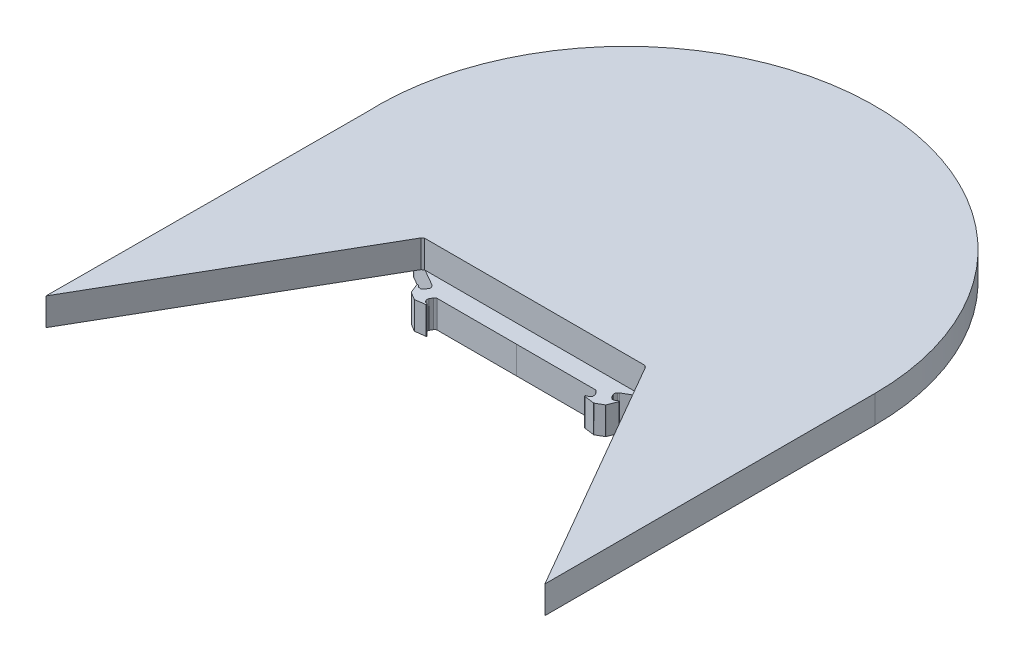
SolidWorks part; units mm, degrees
ref_plane "Plan de face" through (0, 0, 0) normal (0, 0, 1) x (1, 0, 0)
ref_plane "Plan de dessus" through (0, 0, 0) normal (0, 1, 0) x (1, 0, 0)
ref_plane "Plan de droite" through (0, 0, 0) normal (1, 0, 0) x (0, 0, -1)
sketch "Esquisse1" plane through (0, 0, 0) normal (0, 1, 0) x (1, 0, 0)
  line L0 (-45.2608, -54.9089) -> (-45.6072, -54.7089) construction
  line L26 (-150.2608, -236.7743) -> (-20.2608, -11.6077) construction
  line L32 (-20.2608, -11.6077) -> (-20.6666, -11.5106) construction
  line L34 (-0.2608, -11.6077) -> (0.0368, 50.714) construction
  line L35 (-0.2608, -11.6077) -> (-0.2608, -11.2077) construction
  line L38 (-20.2608, -11.6077) -> (19.7392, -11.6077) construction
  line L40 (-45.6072, -54.7089) -> (-20.6666, -11.5106)
  line L41 (-20.2608, -11.6077) -> (-20.2608, -11.2077) construction
  line L53 (-45.6072, -54.7089) -> (-45.3945, 3.1355)
  line L54 (-20.6666, -11.5106) -> (-20.2608, -11.2077)
  line L55 (-20.2608, -11.2077) -> (-0.2608, -11.2077)
  line L56 (19.7392, -11.6077) -> (19.7392, -11.2077) construction
  line L57 (19.7392, -11.6077) -> (20.0857, -11.4077) construction
  line L58 (19.7392, -11.6077) -> (24.7392, -20.2679) construction
  line L59 (44.7392, -54.9089) -> (45.0857, -54.7089) construction
  line L60 (19.7392, -11.6077) -> (149.7392, -236.7743) construction
  line L62 (19.7392, -11.2077) -> (-0.2608, -11.2077)
  line L63 (45.0857, -54.7089) -> (45.0857, 5.2911)
  line L64 (19.7392, -11.2077) -> (20.0857, -11.4077)
  line L65 (20.0857, -11.4077) -> (45.0857, -54.7089)
  arc A0 (-45.3945, 3.1355) -> (45.0857, 5.2911) centre (-0.1801, 5.2911) cw
  dimension "D1" = 50
  dimension "D2" = 90
extrude "Boss.-Extru.1" add sketch "Esquisse1" along normal blind 5
sketch "Esquisse3" plane through (0, 0, 0) normal (0, -1, 0) x (1, 0, 0)
  line L12 (-17.9029, 14.1237) -> (-18.1032, 14.4706) construction
  line L30 (-18.7932, 13.9216) -> (-18.7925, 13.9225) construction
  line L31 (-18.7152, 14.9834) -> (-18.3366, 14.8537) construction
  line L32 (-18.3209, 16.1348) -> (-19.1095, 13.832) construction
  line L33 (-18.2862, 16.1971) -> (-17.9773, 15.9429) construction
  line L34 (-16.5624, 17.1923) -> (-16.5624, 16.7923) construction
  line L35 (-13.9437, 16.5594) -> (-14.3345, 16.4943) construction
  line L36 (-14.9584, 15.8237) -> (-15.1584, 16.1701) construction
  line L37 (-17.4797, 13.7907) -> (-17.1333, 13.9907) construction
  line L38 (-17.6297, 14.0505) -> (-17.3297, 13.5309) construction
  line L39 (-14.8816, 15.2907) -> (-15.228, 15.0907) construction
  line L40 (-14.7316, 15.0309) -> (-15.0316, 15.5505) construction
  line L41 (-17.4306, 16.7057) -> (-17.2327, 16.3629) construction
  line L42 (-16.6295, 17.1682) -> (-18.2317, 16.2432) construction
  line L43 (-15.9306, 14.1077) -> (-20.9306, 22.7679) construction
  line L44 (-17.7511, 14.1437) -> (-17.6487, 14.5257) construction
  line L45 (-15.2967, 16.9571) -> (-15.3494, 16.5594) construction
  line L46 (-14.1025, 16.7228) -> (-16.491, 17.1913) construction
  line L47 (-15.0516, 15.7022) -> (-15.4278, 15.8237) construction
  line L48 (-17.6297, 14.0505) -> (-17.2833, 14.2505) construction
  line L49 (-15.0316, 15.5505) -> (-15.378, 15.3505) construction
  line L50 (-17.1333, 13.9907) -> (-17.2731, 14.2328)
  line L51 (-17.2995, 14.2627) -> (-17.6165, 14.5014)
  line L52 (-17.6887, 14.5208) -> (-18.0751, 14.474)
  line L53 (-18.1253, 14.453) -> (-18.4956, 14.1586)
  line L54 (-18.6506, 14.2743) -> (-17.9898, 15.9119)
  line L55 (-17.9486, 15.9602) -> (-16.5924, 16.7743)
  line L56 (-16.5277, 16.7877) -> (-14.7164, 16.5454)
  line L57 (-14.693, 16.3532) -> (-15.1329, 16.1801)
  line L58 (-15.1752, 16.1485) -> (-15.4031, 15.8555)
  line L59 (-15.4236, 15.7836) -> (-15.3802, 15.3716)
  line L60 (-15.3674, 15.3321) -> (-15.228, 15.0907)
  line L61 (-15.228, 15.0907) -> (-15.0498, 14.782)
  line L62 (-20.2608, 11.6077) -> (-11.6005, 16.6077) construction
  line L63 (-17.1333, 13.9907) -> (-16.9608, 13.692)
  line L66 (-24.5749, 6.5161) -> (23.9303, 6.572)
  line L68 (-20.6666, 11.5106) -> (-20.2608, 11.2077) construction
  line L69 (-20.2608, 11.6077) -> (-20.0679, 11.2736) construction
  line L70 (-20.2608, 11.6077) -> (-25.2608, 20.2679) construction
  line L71 (-17.4029, 13.2577) -> (-17.21, 12.9236) construction
  line L73 (-25.076, 8.3821) -> (-17.2804, 12.8829)
  line L74 (-17.3097, 13.3791) -> (-16.9455, 13.2743) construction
  line L75 (-17.161, 12.9885) -> (-16.9981, 13.2046)
  line L76 (-16.9267, 13.3596) -> (-16.9165, 13.4062)
  line L77 (-14.8435, 14.6074) -> (-14.7364, 14.5673)
  line L79 (-14.5066, 15.324) -> (-14.6686, 14.542) construction
  line L80 (-14.5963, 14.542) -> (-0.2608, 14.542)
  line L81 (-0.2608, 11.6077) -> (-0.2608, 28.9666) construction
  line L82 (-0.2608, 14.542) -> (-0.3638, 6.544) construction
  line L84 (19.566, 11.7077) -> (19.366, 11.3612) construction
  line L85 (16.8814, 13.2577) -> (16.6814, 12.9112) construction
  line L86 (16.7882, 13.3791) -> (16.4018, 13.2756) construction
  line L87 (16.8082, 13.5309) -> (16.4618, 13.7309) construction
  line L88 (16.8082, 13.5309) -> (17.1082, 14.0505) construction
  line L89 (17.1082, 14.0505) -> (16.7618, 14.2505) construction
  line L90 (17.2296, 14.1437) -> (17.1261, 14.53) construction
  line L91 (17.3814, 14.1237) -> (17.5814, 14.4701) construction
  line L92 (18.2717, 13.9216) -> (18.271, 13.9225) construction
  line L93 (17.7994, 16.1348) -> (17.421, 16.0052) construction
  line L94 (18.588, 13.832) -> (17.7994, 16.1348) construction
  line L95 (15.9695, 17.1913) -> (16.0465, 16.7988) construction
  line L96 (13.4222, 16.5594) -> (13.8167, 16.4937) construction
  line L97 (14.4369, 15.8237) -> (14.6369, 16.1701) construction
  line L98 (14.5301, 15.7022) -> (14.9164, 15.8058) construction
  line L99 (14.5101, 15.5505) -> (14.8565, 15.3505) construction
  line L100 (14.2101, 15.0309) -> (14.5565, 14.8309) construction
  line L101 (13.9851, 15.324) -> (14.1922, 14.5513) construction
  line L102 (14.2191, 14.5719) -> (14.5407, 14.8188)
  line L103 (14.5664, 14.8481) -> (14.8465, 15.3332)
  line L104 (14.8591, 15.3702) -> (14.911, 15.7647)
  line L105 (14.8912, 15.8386) -> (14.6537, 16.1481)
  line L106 (14.6111, 16.1803) -> (14.1723, 16.3534)
  line L107 (14.1954, 16.5455) -> (16.0126, 16.7941)
  line L108 (16.0762, 16.7817) -> (17.3914, 16.0223)
  line L109 (17.4339, 15.9735) -> (18.1267, 14.2761)
  line L110 (17.9719, 14.16) -> (17.603, 14.4529)
  line L111 (17.5539, 14.4737) -> (17.1671, 14.5246)
  line L112 (17.0932, 14.5048) -> (16.7775, 14.2626)
  line L113 (16.7518, 14.2332) -> (16.4717, 13.7481)
  line L114 (16.4592, 13.7111) -> (16.4397, 13.563)
  line L115 (16.5783, 13.0455) -> (16.5966, 13.0217)
  line L116 (16.802, 12.8416) -> (24.4291, 8.4381)
  line L118 (14.1583, 14.5513) -> (-0.2608, 14.542)
  arc A4 (-19.1095, 13.832) -> (-18.8203, 13.594) centre (-18.9203, 13.7672) ccw construction
  arc A5 (-18.2317, 16.2432) -> (-18.3209, 16.1348) centre (-18.1317, 16.07) ccw construction
  arc A6 (-16.491, 17.1913) -> (-16.6295, 17.1682) centre (-16.5295, 16.995) ccw construction
  arc A7 (-14.041, 16.3534) -> (-14.1025, 16.7228) centre (-14.141, 16.5266) ccw construction
  arc A8 (-17.6297, 14.0505) -> (-17.9029, 14.1237) centre (-17.8029, 13.9505) ccw construction
  arc A9 (-14.9584, 15.8237) -> (-15.0316, 15.5505) centre (-14.8584, 15.6505) ccw construction
  arc A10 (-15.1752, 16.1485) -> (-15.1329, 16.1801) centre (-15.0963, 16.0871) cw
  arc A11 (-15.4236, 15.7836) -> (-15.4031, 15.8555) centre (-15.3242, 15.7941) cw
  arc A12 (-15.3674, 15.3321) -> (-15.3802, 15.3716) centre (-15.2808, 15.3821) cw
  arc A13 (-17.2995, 14.2627) -> (-17.2731, 14.2328) centre (-17.3597, 14.1828) cw
  arc A14 (-17.6887, 14.5208) -> (-17.6165, 14.5014) centre (-17.6767, 14.4216) cw
  arc A15 (-18.1253, 14.453) -> (-18.0751, 14.474) centre (-18.063, 14.3747) cw
  arc A16 (-16.5924, 16.7743) -> (-16.5277, 16.7877) centre (-16.5409, 16.6886) cw
  arc A17 (-17.9898, 15.9119) -> (-17.9486, 15.9602) centre (-17.8971, 15.8744) cw
  arc A18 (-14.7164, 16.5454) -> (-14.693, 16.3532) centre (-14.7297, 16.4463) cw
  arc A19 (-18.6506, 14.2743) -> (-18.4956, 14.1586) centre (-18.5578, 14.2368) ccw
  arc A20 (-17.4029, 13.2577) -> (-17.3297, 13.5309) centre (-17.5029, 13.4309) ccw construction
  arc A22 (-16.9267, 13.3596) -> (-16.9981, 13.2046) centre (-17.3174, 13.4454) cw
  arc A23 (-17.161, 12.9885) -> (-17.2804, 12.8829) centre (-17.4804, 13.2293) cw
  arc A24 (-16.9608, 13.692) -> (-16.9165, 13.4062) centre (-17.3072, 13.492) cw
  arc A25 (-14.7316, 15.0309) -> (-14.4584, 14.9577) centre (-14.5584, 15.1309) ccw construction
  arc A26 (-14.5963, 14.542) -> (-14.7364, 14.5673) centre (-14.5963, 14.942) cw
  arc A27 (-15.0498, 14.782) -> (-14.8435, 14.6074) centre (-14.7034, 14.982) ccw
  arc A28 (24.4291, 8.4381) -> (23.9303, 6.572) centre (23.9291, 7.572) cw
  arc A29 (16.8082, 13.5309) -> (16.8814, 13.2577) centre (16.9814, 13.4309) ccw construction
  arc A30 (17.3814, 14.1237) -> (17.1082, 14.0505) centre (17.2814, 13.9505) ccw construction
  arc A31 (18.2988, 13.594) -> (18.588, 13.832) centre (18.3988, 13.7672) ccw construction
  arc A32 (13.581, 16.7228) -> (13.5195, 16.3534) centre (13.6195, 16.5266) ccw construction
  arc A33 (14.5101, 15.5505) -> (14.4369, 15.8237) centre (14.3369, 15.6505) ccw construction
  arc A34 (13.9369, 14.9577) -> (14.2101, 15.0309) centre (14.0369, 15.1309) ccw construction
  arc A35 (16.5783, 13.0455) -> (16.4397, 13.563) centre (17.1337, 13.4717) cw
  arc A36 (16.802, 12.8416) -> (16.5966, 13.0217) centre (17.152, 13.4478) cw
  arc A39 (14.8591, 15.3702) -> (14.8465, 15.3332) centre (14.7599, 15.3832) cw
  arc A40 (14.1583, 14.5513) -> (14.2191, 14.5719) centre (14.1582, 14.6513) ccw
  arc A41 (14.5664, 14.8481) -> (14.5407, 14.8188) centre (14.4798, 14.8981) cw
  arc A42 (14.8912, 15.8386) -> (14.911, 15.7647) centre (14.8119, 15.7778) cw
  arc A43 (14.6111, 16.1803) -> (14.6537, 16.1481) centre (14.5744, 16.0872) cw
  arc A44 (14.1954, 16.5455) -> (14.1723, 16.3534) centre (14.209, 16.4464) ccw
  arc A45 (16.0762, 16.7817) -> (16.0126, 16.7941) centre (16.0262, 16.6951) ccw
  arc A46 (17.4339, 15.9735) -> (17.3914, 16.0223) centre (17.3414, 15.9357) ccw
  arc A47 (16.4592, 13.7111) -> (16.4717, 13.7481) centre (16.5583, 13.6981) cw
  arc A48 (16.7518, 14.2332) -> (16.7775, 14.2626) centre (16.8384, 14.1832) cw
  arc A49 (17.0932, 14.5048) -> (17.1671, 14.5246) centre (17.1541, 14.4255) cw
  arc A50 (17.5539, 14.4737) -> (17.603, 14.4529) centre (17.5409, 14.3746) cw
  arc A51 (17.9719, 14.16) -> (18.1267, 14.2761) centre (18.0341, 14.2383) ccw
  arc A55 (-25.076, 8.3821) -> (-24.5749, 6.5161) centre (-24.576, 7.5161) ccw
  point P113 (0, 0)
  point P134 (-20.2748, 11.2181)
  point P143 (-16.8833, 13.5577)
  point P157 (-14.978, 14.6577)
  point P160 (0, 0)
  point P236 (19.7392, 11.2077)
  point P285 (20.0857, 11.4077)
  dimension "D1" = 90
  dimension "D2" = 90
  dimension "D3" = 0.1
  dimension "D5" = 1
  dimension "D6" = 0.4
  dimension "D9" = 0.7
  dimension "D10" = 0.1
  dimension "D4" = 180
  dimension "D7" = 90
  dimension "D8" = 90
extrude "Boss.-Extru.2" add sketch "Esquisse3" along normal blind 5
